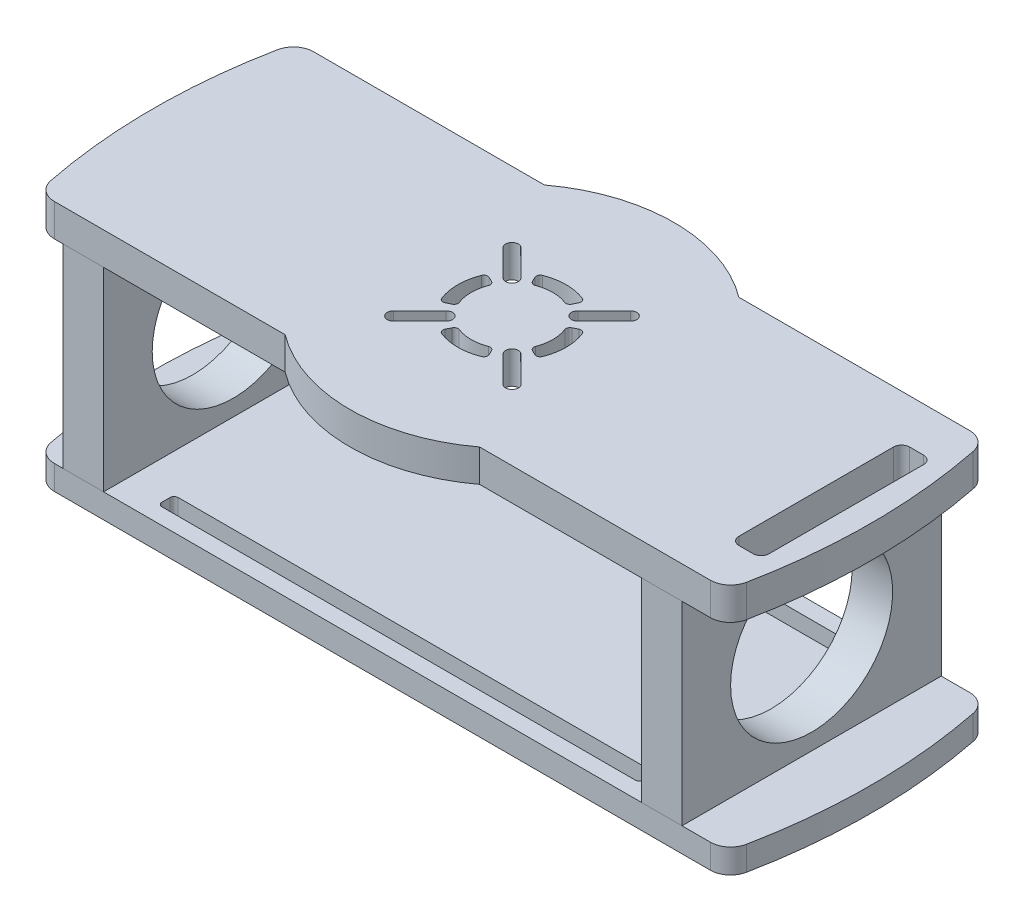
SolidWorks part; units mm, degrees
ref_plane "Front Plane" through (0, 0, 0) normal (0, 0, 1) x (1, 0, 0)
ref_plane "Top Plane" through (0, 0, 0) normal (0, 1, 0) x (1, 0, 0)
ref_plane "Right Plane" through (0, 0, 0) normal (1, 0, 0) x (0, 0, -1)
sketch "Sketch3" plane through (0, 0, 0) normal (0, 1, 0) x (1, 0, 0)
  line L0 (-12, -16) -> (-42.5, -16)
  line L5 (12, 16) -> (42.5, 16)
  line L7 (-42.5, 16) -> (-12, 16)
  line L9 (42.5, -16) -> (12, -16)
  line L12 (37.544, -10.5318) -> (41.2787, -10.5318)
  line L13 (37.544, -10.5318) -> (37.544, 10.5318)
  line L14 (37.544, 10.5318) -> (41.2787, 10.5318)
  line L15 (41.2787, -10.5318) -> (41.2787, 10.5318)
  arc A0 (-12, -16) -> (12, -16) centre (0, 0) ccw
  arc A1 (12, 16) -> (-12, 16) centre (0, 0) ccw
  arc A2 (-42.5, 16) -> (-42.5, -16) centre (27.2487, 0) ccw
  arc A3 (42.5, 16) -> (42.5, -16) centre (-27.2487, 0) cw
  point P3 (0, 0)
  point P6 (0, 0)
extrude "Boss-Extrude1" add sketch "Sketch3" along normal blind 4
sketch "Sketch4" plane through (0, 0, 0) normal (0, -1, 0) x (1, 0, 0)
  line L0 (-39.4047, 16) -> (-39.4047, -16)
  line L1 (-39.4047, -16) -> (-34.4047, -16)
  line L2 (-34.4047, -16) -> (-34.4047, 16)
  line L3 (-34.4047, 16) -> (-39.4047, 16)
  line L5 (31.9796, -16) -> (31.9796, 16)
  line L6 (36.9796, -16) -> (31.9796, -16)
  line L7 (36.9796, 16) -> (36.9796, -16)
  line L8 (31.9796, 16) -> (36.9796, 16)
extrude "Boss-Extrude2" add sketch "Sketch4" along normal blind 24 separate body
sketch "Sketch5" plane through (0, -24, 0) normal (0, -1, 0) x (1, 0, 0)
  line L24 (-12, 16) -> (12, 16)
  line L25 (-12, -16) -> (12, -16)
  line L26 (-42.5, 16) -> (-12, 16)
  line L27 (12, 16) -> (42.5, 16)
  line L28 (42.5, -16) -> (12, -16)
  line L29 (-12, -16) -> (-42.5, -16)
  arc A0 (42.5, -16) -> (42.5, 16) centre (-27.2487, 0) ccw construction
  arc A1 (-42.5, 16) -> (-42.5, -16) centre (27.2487, 0) ccw construction
  arc A2 (42.5, -16) -> (42.5, 16) centre (-27.2487, 0) ccw
  arc A3 (-42.5, 16) -> (-42.5, -16) centre (27.2487, 0) ccw
extrude "Boss-Extrude3" add sketch "Sketch5" along normal blind 3 separate body
sketch "Sketch6" plane through (0, -27, 0) normal (0, -1, 0) x (1, 0, 0)
  line L1 (-29.1996, -12) -> (29.1996, -12)
  line L2 (-29.1996, 14) -> (29.1996, 14)
  line L3 (-29.6996, 13.5) -> (-29.6996, 12.5)
  line L4 (-29.1996, 12) -> (29.1996, 12)
  line L5 (29.6996, 13.5) -> (29.6996, 12.5)
  line L6 (29.6996, -13.5) -> (29.6996, -12.5)
  line L7 (-29.1996, -14) -> (29.1996, -14)
  line L8 (-29.6996, -13.5) -> (-29.6996, -12.5)
  arc A0 (29.6996, 12.5) -> (29.1996, 12) centre (29.1996, 12.5) cw
  arc A1 (29.1996, 14) -> (29.6996, 13.5) centre (29.1996, 13.5) cw
  arc A2 (-29.1996, 12) -> (-29.6996, 12.5) centre (-29.1996, 12.5) cw
  arc A3 (-29.1996, 14) -> (-29.6996, 13.5) centre (-29.1996, 13.5) ccw
  arc A4 (29.6996, -12.5) -> (29.1996, -12) centre (29.1996, -12.5) ccw
  arc A5 (29.1996, -14) -> (29.6996, -13.5) centre (29.1996, -13.5) ccw
  arc A6 (-29.1996, -12) -> (-29.6996, -12.5) centre (-29.1996, -12.5) ccw
  arc A7 (-29.1996, -14) -> (-29.6996, -13.5) centre (-29.1996, -13.5) cw
  dimension "D1" = 0.5
extrude "Cut-Extrude1" cut sketch "Sketch6" against normal blind 3
fillet "Fillet3" radius 2.5 4 edges at (42.5, -25.5, -16) (42.5, -25.5, 16) (-42.5, -25.5, -16) (-42.5, -25.5, 16)
fillet "Fillet4" radius 2.5 4 edges at (42.5, 2, 16) (-42.5, 2, 16) (-42.5, 2, -16) (42.5, 2, -16)
fillet "Fillet5" radius 1 4 edges at (41.2787, 2, 10.5318) (37.544, 2, 10.5318) (41.2787, 2, -10.5318) (37.544, 2, -10.5318)
sketch "Sketch7" plane through (0, 4, 0) normal (0, 1, 0) x (1, 0, 0)
  line L0 (4.0618, -4.0618) -> (7.3047, -7.3047) construction
  line L1 (4.6142, -3.5094) -> (7.8571, -6.7523)
  line L2 (3.5094, -4.6142) -> (6.7523, -7.8571)
  line L3 (-4.0618, -4.0618) -> (-7.3047, -7.3047) construction
  line L4 (-2.4326, 4.954) -> (-2.7202, 5.5395)
  line L5 (2.4323, 4.9541) -> (2.7199, 5.5397)
  line L6 (4.954, 2.4326) -> (5.5395, 2.7202)
  line L7 (4.9541, -2.4323) -> (5.5397, -2.7199)
  line L8 (2.4326, -4.954) -> (2.7202, -5.5395)
  line L9 (-2.4323, -4.9541) -> (-2.7199, -5.5397)
  line L10 (-4.954, -2.4326) -> (-5.5395, -2.7202)
  line L11 (-4.9541, 2.4323) -> (-5.5397, 2.7199)
  line L12 (4.0618, 4.0618) -> (7.3047, 7.3047) construction
  line L13 (3.5094, 4.6142) -> (6.7523, 7.8571)
  line L14 (4.6142, 3.5094) -> (7.8571, 6.7523)
  line L15 (-3.5094, -4.6142) -> (-6.7523, -7.8571)
  line L16 (-4.6142, -3.5094) -> (-7.8571, -6.7523)
  line L17 (-4.0618, 4.0618) -> (-7.3047, 7.3047) construction
  line L18 (-4.6142, 3.5094) -> (-7.8571, 6.7523)
  line L19 (-3.5094, 4.6142) -> (-6.7523, 7.8571)
  arc A2 (2.4544, 6.2252) -> (-2.4548, 6.2251) centre (0, 0) ccw
  arc A3 (1.8046, 4.7076) -> (-1.8048, 4.7075) centre (0, 0) ccw
  arc A4 (2.7199, 5.5397) -> (2.4544, 6.2252) centre (2.271, 5.76) ccw
  arc A5 (2.4323, 4.9541) -> (1.8046, 4.7076) centre (1.9835, 5.1745) cw
  arc A6 (-1.8048, 4.7075) -> (-2.4326, 4.954) centre (-1.9838, 5.1743) cw
  arc A7 (-2.7202, 5.5395) -> (-2.4548, 6.2251) centre (-2.2714, 5.7599) cw
  arc A8 (5.5395, 2.7202) -> (6.2251, 2.4548) centre (5.7599, 2.2714) cw
  arc A9 (4.7075, 1.8048) -> (4.954, 2.4326) centre (5.1743, 1.9838) cw
  arc A10 (6.2252, -2.4544) -> (6.2251, 2.4548) centre (0, 0) ccw
  arc A11 (5.5397, -2.7199) -> (6.2252, -2.4544) centre (5.76, -2.271) ccw
  arc A12 (4.9541, -2.4323) -> (4.7076, -1.8046) centre (5.1745, -1.9835) cw
  arc A13 (4.7076, -1.8046) -> (4.7075, 1.8048) centre (0, 0) ccw
  arc A14 (2.7202, -5.5395) -> (2.4548, -6.2251) centre (2.2714, -5.7599) cw
  arc A15 (1.8048, -4.7075) -> (2.4326, -4.954) centre (1.9838, -5.1743) cw
  arc A16 (-2.4544, -6.2252) -> (2.4548, -6.2251) centre (0, 0) ccw
  arc A17 (-2.7199, -5.5397) -> (-2.4544, -6.2252) centre (-2.271, -5.76) ccw
  arc A18 (-2.4323, -4.9541) -> (-1.8046, -4.7076) centre (-1.9835, -5.1745) cw
  arc A19 (-1.8046, -4.7076) -> (1.8048, -4.7075) centre (0, 0) ccw
  arc A20 (-5.5395, -2.7202) -> (-6.2251, -2.4548) centre (-5.7599, -2.2714) cw
  arc A21 (-4.7075, -1.8048) -> (-4.954, -2.4326) centre (-5.1743, -1.9838) cw
  arc A22 (-6.2252, 2.4544) -> (-6.2251, -2.4548) centre (0, 0) ccw
  arc A23 (-5.5397, 2.7199) -> (-6.2252, 2.4544) centre (-5.76, 2.271) ccw
  arc A24 (-4.9541, 2.4323) -> (-4.7076, 1.8046) centre (-5.1745, 1.9835) cw
  arc A25 (-4.7076, 1.8046) -> (-4.7075, -1.8048) centre (0, 0) ccw
  arc A26 (3.5094, 4.6142) -> (4.6142, 3.5094) centre (4.0618, 4.0618) ccw
  arc A27 (7.8571, 6.7523) -> (6.7523, 7.8571) centre (7.3047, 7.3047) ccw
  arc A28 (4.6142, -3.5094) -> (3.5094, -4.6142) centre (4.0618, -4.0618) ccw
  arc A29 (6.7523, -7.8571) -> (7.8571, -6.7523) centre (7.3047, -7.3047) ccw
  arc A30 (-3.5094, -4.6142) -> (-4.6142, -3.5094) centre (-4.0618, -4.0618) ccw
  arc A31 (-7.8571, -6.7523) -> (-6.7523, -7.8571) centre (-7.3047, -7.3047) ccw
  arc A32 (-4.6142, 3.5094) -> (-3.5094, 4.6142) centre (-4.0618, 4.0618) ccw
  arc A33 (-6.7523, 7.8571) -> (-7.8571, 6.7523) centre (-7.3047, 7.3047) ccw
  point P9 (0, 0)
  point P56 (0, 0)
  point P57 (5.6833, 5.6833)
  point P63 (5.6833, -5.6833)
  point P70 (-5.6833, -5.6833)
  point P77 (-5.6833, 5.6833)
  point P82 (0, 0)
  dimension "D1" = 4
  dimension "D4" = 0.5
  dimension "D5" = 4
extrude "Cut-Extrude2" cut sketch "Sketch7" against normal up to surface (4 mm away) up to face at (0, 0, 0)
sketch "Sketch8" plane through (-39.4047, 0, 0) normal (-1, 0, 0) x (0, 0, 1)
  circle A0 centre (0, -12) radius 10
extrude "Cut-Extrude3" cut sketch "Sketch8" against normal up to surface (76.3843 mm away)
